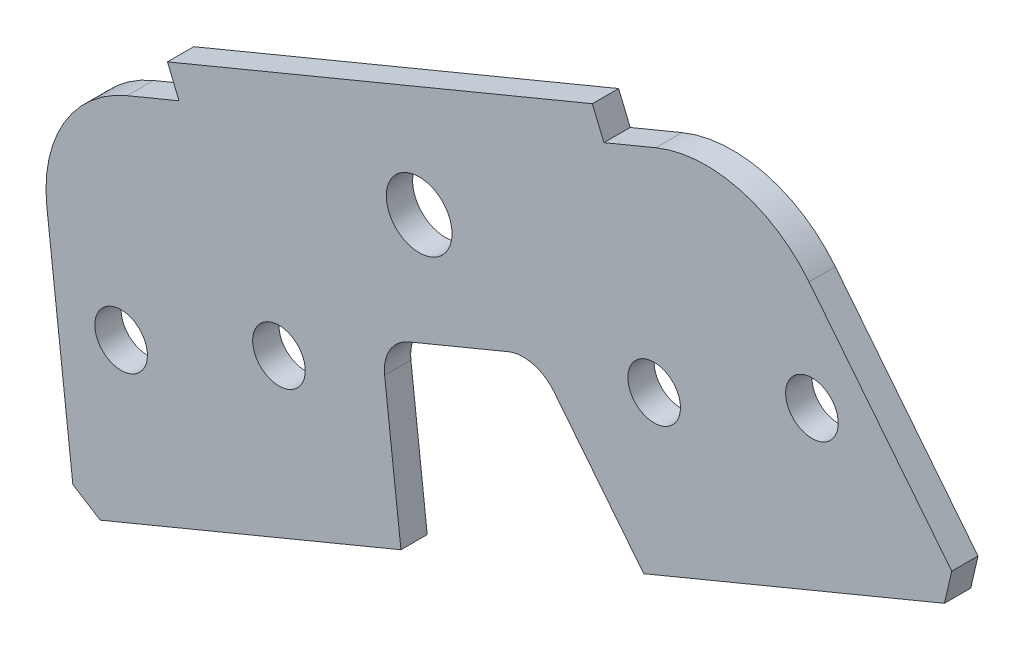
SolidWorks part; units mm, degrees
material "Thornel Mat VMA"
ref_plane "前视基准面" through (0, 0, 0) normal (0, 0, 1) x (1, 0, 0)
ref_plane "上视基准面" through (0, 0, 0) normal (0, 1, 0) x (1, 0, 0)
ref_plane "右视基准面" through (0, 0, 0) normal (1, 0, 0) x (0, 0, -1)
sketch "草图1" plane through (0, 0, 0) normal (0, 0, 1) x (1, 0, 0)
  line L1 (-89.0519, 56.3159) -> (89.0519, 56.3159)
  line L2 (-89.0519, 56.3159) -> (-89.0519, -56.3159)
  line L3 (-89.0519, -56.3159) -> (89.0519, -56.3159)
  line L4 (89.0519, 56.3159) -> (89.0519, -56.3159)
  line L5 (-89.0519, 56.3159) -> (89.0519, -56.3159) construction
  line L6 (-89.0519, -56.3159) -> (89.0519, 56.3159) construction
  point P0 (0, 0)
extrude "凸台-拉伸1" add sketch "草图1" along normal blind 2
sketch "草图2" plane through (0, 0, 2) normal (0, 0, 1) x (1, 0, 0)
  line L10 (19.4197, -9.0084) -> (26.2403, -17.5761)
  line L11 (19.4197, -9.0084) -> (26.2403, -17.5761)
  line L12 (7.7658, -25.2371) -> (6.5217, -14.3568)
  line L13 (26.2403, -17.5761) -> (49.1204, -8.0882)
  line L14 (49.1204, -8.0882) -> (49.6721, -5.6944)
  line L15 (49.6721, -5.6944) -> (38.8152, 7.9435)
  line L16 (27.1611, 10.9525) -> (23.209, 9.3137)
  line L17 (-19.1784, -16.1051) -> (-17.1982, -33.4239)
  line L18 (-17.1982, -33.4239) -> (-15.1144, -34.725)
  line L19 (-15.1144, -34.725) -> (7.7658, -25.2371)
  line L23 (26.2403, -17.5761) -> (49.1204, -8.0882)
  line L24 (49.1204, -8.0882) -> (49.6721, -5.6944)
  line L25 (49.6721, -5.6944) -> (38.8152, 7.9435)
  line L26 (27.1611, 10.9525) -> (23.209, 9.3137)
  line L27 (-19.1784, -16.1051) -> (-17.1982, -33.4239)
  line L28 (-17.1982, -33.4239) -> (-15.1144, -34.725)
  line L29 (-15.1144, -34.725) -> (7.7658, -25.2371)
  line L50 (7.7658, -25.2371) -> (6.5217, -14.3568)
  line L51 (8.3532, -11.2449) -> (15.9234, -8.1056)
  line L52 (8.3532, -11.2449) -> (15.9234, -8.1056)
  line L61 (23.209, 9.3137) -> (22.328, 11.4383)
  line L62 (23.209, 9.3137) -> (22.328, 11.4383)
  line L63 (22.328, 11.4383) -> (-10.0025, -1.9685)
  line L64 (22.328, 11.4383) -> (-10.0025, -1.9685)
  line L65 (-10.0025, -1.9685) -> (-9.1215, -4.093)
  line L66 (-10.0025, -1.9685) -> (-9.1215, -4.093)
  line L67 (-9.1215, -4.093) -> (-13.0736, -5.7319)
  line L68 (-9.1215, -4.093) -> (-13.0736, -5.7319)
  arc A6 (8.3532, -11.2449) -> (6.5217, -14.3568) centre (9.5023, -14.016) ccw
  arc A7 (8.3532, -11.2449) -> (6.5217, -14.3568) centre (9.5023, -14.016) ccw
  arc A8 (19.4197, -9.0084) -> (15.9234, -8.1056) centre (17.0726, -10.8768) ccw
  arc A9 (19.4197, -9.0084) -> (15.9234, -8.1056) centre (17.0726, -10.8768) ccw
  arc A10 (38.8152, 7.9435) -> (27.1611, 10.9525) centre (30.9916, 1.7152) ccw
  arc A11 (-13.0736, -5.7319) -> (-19.1784, -16.1051) centre (-9.2431, -14.9692) ccw
  arc A16 (38.8152, 7.9435) -> (27.1611, 10.9525) centre (30.9916, 1.7152) ccw
  arc A17 (-13.0736, -5.7319) -> (-19.1784, -16.1051) centre (-9.2431, -14.9692) ccw
  dimension "D1" = 0
extrude "切除-拉伸1" cut sketch "草图2" against normal blind 2 flip side to cut
sketch "草图3" plane through (0, 0, 2) normal (0, 0, 1) x (1, 0, 0)
  circle A0 centre (39.0393, -0.2662) radius 2 construction
  circle A1 centre (-13.5269, -22.0643) radius 2 construction
  circle A2 centre (39.0393, -0.2662) radius 2
  circle A3 centre (-13.5269, -22.0643) radius 2
extrude "切除-拉伸2" cut sketch "草图3" against normal blind 2
sketch "草图4" plane through (0, 0, 2) normal (0, 0, 1) x (1, 0, 0)
  circle A0 centre (-1.5185, -17.0846) radius 2 construction
  circle A1 centre (27.0308, -5.2459) radius 2 construction
  circle A2 centre (-1.5185, -17.0846) radius 2
  circle A3 centre (27.0308, -5.2459) radius 2
extrude "切除-拉伸3" cut sketch "草图4" against normal blind 10
sketch "草图5" plane through (0, 0, 2) normal (0, 0, 1) x (1, 0, 0)
  circle A0 centre (9.1505, -2.4702) radius 2.5 construction
  circle A1 centre (9.1505, -2.4702) radius 2.5
extrude "切除-拉伸4" cut sketch "草图5" against normal blind 10
